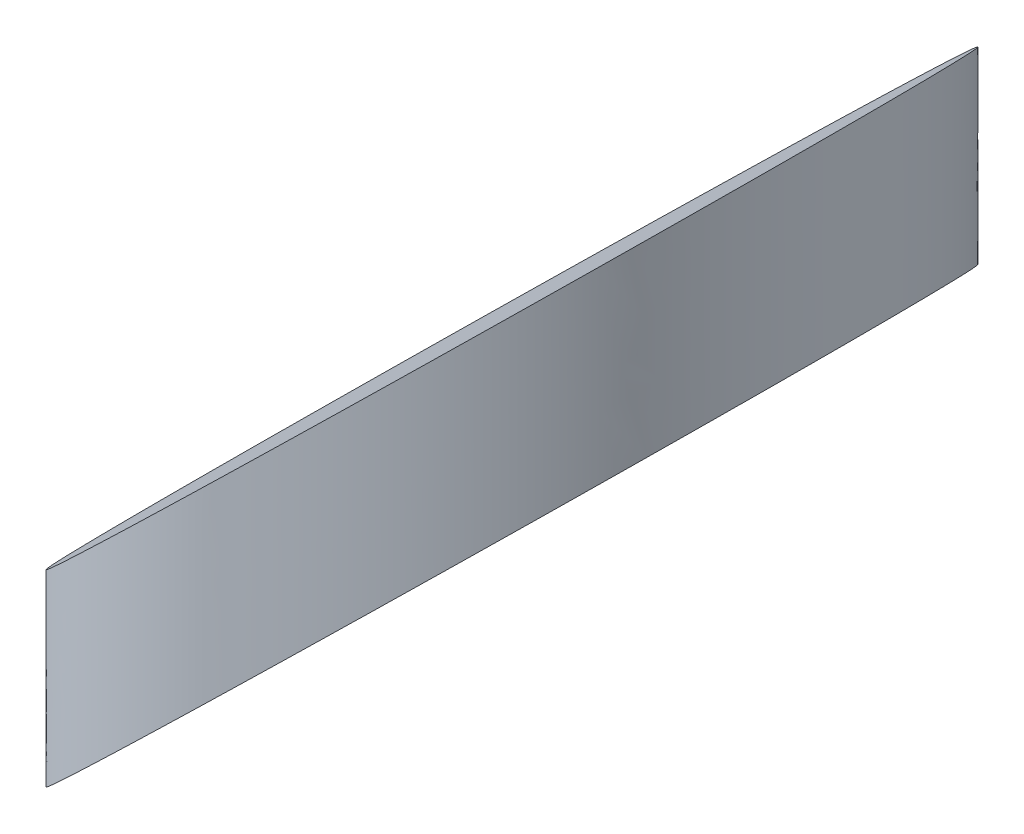
SolidWorks part; units mm, degrees
ref_plane "Спереди" through (0, 0, 0) normal (0, 0, 1) x (1, 0, 0)
ref_plane "Сверху" through (0, 0, 0) normal (0, 1, 0) x (1, 0, 0)
ref_plane "Справа" through (0, 0, 0) normal (1, 0, 0) x (0, 0, -1)
sketch "Эскиз3" plane through (0, 0, 0) normal (0, 1, 0) x (1, 0, 0)
  ellipse E0 centre (0, 0) end of major axis (17.5, 0) minor radius 17.5
  dimension "D1" = 35
  dimension "D2" = 35
extrude "Бобышка-Вытянуть2" add sketch "Эскиз3" along normal blind 44
sketch "Эскиз4" plane through (0, 0, 0) normal (0, 0, 1) x (1, 0, 0)
  line L0 (17.5, 44) -> (17.5, 34)
  line L1 (17.5, 0) -> (17.5, 44) construction
  line L2 (17.5, 34) -> (-17.5, 0)
  line L3 (-17.5, 0) -> (-17.5, 10)
  line L4 (-17.5, 44) -> (-17.5, 0) construction
  line L5 (-17.5, 10) -> (17.5, 44)
  line L6 (-17.5, 10) -> (-17.5, 44)
  line L7 (-17.5, 44) -> (17.5, 44)
  line L8 (17.5, 34) -> (17.5, 0)
  line L9 (17.5, 0) -> (-17.5, 0)
  dimension "D1" = 10
  dimension "D2" = 10
extrude "Вырез-Вытянуть2" cut sketch "Эскиз4" against normal through all and the other way through all contours L7 L6 L5 | L9 L8 L2
sketch "Эскиз5" plane through (-8.4964, 8.7463, 0) normal (0.6968, -0.7173, 0) x (0.7173, 0.6968, 0)
  line L0 (-12.5524, 0) -> (36.2431, 0) construction
  line L1 (11.8454, -17.5) -> (11.8454, 17.5) construction
  ellipse E0 centre (11.8454, 0) end of major axis (-12.5524, 0) minor radius 17.5 construction
sketch "Эскиз7" plane through (0, 0, 0) normal (0, 0, 1) x (1, 0, 0)
  line L0 (-17.5, 0) -> (0, 0) construction
sketch "Эскиз8" plane through (0, 0, 0) normal (0, 0, 1) x (1, 0, 0)
  line L2 (-17.5, 0) -> (17.5, 34) construction
  line L4 (-17.5, 0) -> (0, -0.2536) construction
  line L5 (0, 0) -> (0, -0.2536) construction
  line L6 (17.5, 34) -> (-17.5, 34) construction
  line L7 (-17.5, 34) -> (-17.5, 0) construction
  line L8 (0, 34) -> (0, 0) construction
  point P1 (0, 17)
  point P10 (0, 0)
  dimension "D1" = 45
  dimension "D2" = 17.2536
